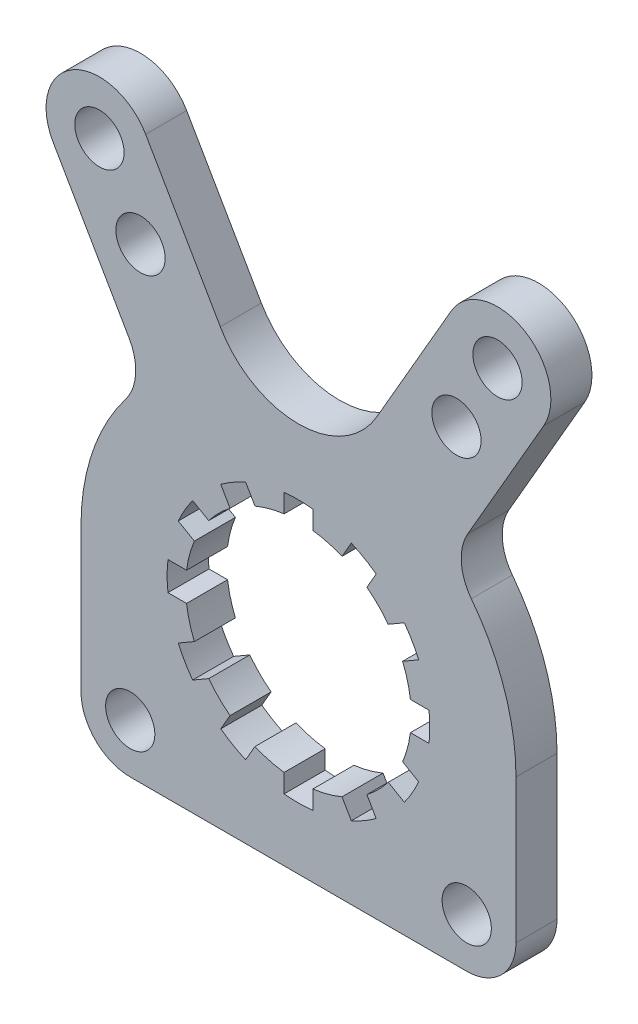
SolidWorks part; units mm, degrees
ref_plane "Alzado" through (0, 0, 0) normal (0, 0, 1) x (1, 0, 0)
ref_plane "Planta" through (0, 0, 0) normal (0, 1, 0) x (1, 0, 0)
ref_plane "Vista lateral" through (0, 0, 0) normal (1, 0, 0) x (0, 0, -1)
sketch "Croquis1" plane through (0, 0, 0) normal (0, 0, 1) x (1, 0, 0)
  line L0 (-59.7583, 77.5045) -> (-41.2583, 45.4615)
  line L5 (0, -79.3293) -> (0, 79.3293) construction
  line L7 (-99.8254, 0) -> (99.8254, 0) construction
  line L8 (-53, 0) -> (-53, -35)
  line L9 (-41, -47) -> (41, -47)
  line L11 (-48.5, 84.0045) -> (0, 0) construction
  line L12 (-37.2417, 90.5045) -> (-19.0526, 59)
  line L13 (37.2417, 90.5045) -> (19.0526, 59)
  line L14 (53, 0) -> (53, -35)
  line L15 (59.7583, 77.5045) -> (41.2583, 45.4615)
  arc A0 (-53, -35) -> (-41, -47) centre (-41, -35) ccw
  circle A8 centre (0, 0) radius 41 construction
  arc A10 (-37.2417, 90.5045) -> (-59.7583, 77.5045) centre (-48.5, 84.0045) ccw
  arc A11 (-41.2583, 45.4615) -> (-42.1151, 32.1763) centre (-51.6506, 39.4615) cw
  arc A12 (-42.1151, 32.1763) -> (-53, 0) centre (0, 0) ccw
  arc A13 (42.1151, 32.1763) -> (53, 0) centre (0, 0) cw
  arc A14 (41.2583, 45.4615) -> (42.1151, 32.1763) centre (51.6506, 39.4615) ccw
  arc A15 (37.2417, 90.5045) -> (59.7583, 77.5045) centre (48.5, 84.0045) cw
  arc A16 (53, -35) -> (41, -47) centre (41, -35) cw
  arc A17 (-19.0526, 59) -> (19.0526, 59) centre (0, 70) ccw
  circle A18 centre (0, 0) radius 53 construction
  point P2 (-38.5, 66.684)
  point P3 (-26.5, 45.8993)
  point P14 (0, -47)
  point P17 (0, 0)
  point P18 (-20.5, 35.507)
  point P22 (0, 0)
  point P35 (20.5, 35.507)
  point P36 (26.5, 45.8993)
  point P37 (38.5, 66.684)
  point P38 (0, 0)
  dimension "D1" = 24
  dimension "D2" = 24
  dimension "D4" = 82
  dimension "D5" = 13
  dimension "D7" = 82
  dimension "D8" = 12
  dimension "D3" = 20
  dimension "D11" = 22
  dimension "D6" = 30
  dimension "D9" = 35
extrude "Saliente-Extruir1" add sketch "Croquis1" along normal blind 10
sketch "Croquis2" plane through (0, 0, 10) normal (0, 0, 1) x (1, 0, 0)
  line L0 (-3.5, 31.808) -> (-3.5, 27.2764)
  line L1 (3.5, 31.808) -> (3.5, 27.2764)
  line L2 (-3.5, 29.5422) -> (3.5, 29.5422) construction
  line L3 (18.9351, 25.7966) -> (16.6693, 21.872)
  line L4 (12.8729, 29.2966) -> (10.6071, 25.372)
  line L5 (29.2966, 12.8729) -> (25.372, 10.6071)
  line L6 (25.7966, 18.9351) -> (21.872, 16.6693)
  line L7 (-53, 0) -> (-53, -35)
  line L8 (-41, -47) -> (41, -47)
  line L9 (53, -35) -> (53, 0)
  line L10 (41.2583, 45.4615) -> (59.7583, 77.5045)
  line L11 (37.2417, 90.5045) -> (19.0526, 59)
  line L12 (-19.0526, 59) -> (-37.2417, 90.5045)
  line L13 (-59.7583, 77.5045) -> (-41.2583, 45.4615)
  line L14 (-53, 0) -> (-53, -35)
  line L15 (-41, -47) -> (41, -47)
  line L16 (53, -35) -> (53, 0)
  line L17 (41.2583, 45.4615) -> (59.7583, 77.5045)
  line L18 (37.2417, 90.5045) -> (19.0526, 59)
  line L19 (-19.0526, 59) -> (-37.2417, 90.5045)
  line L20 (-59.7583, 77.5045) -> (-41.2583, 45.4615)
  line L21 (31.808, -3.5) -> (27.2764, -3.5)
  line L22 (31.808, 3.5) -> (27.2764, 3.5)
  line L23 (25.7966, -18.9351) -> (21.872, -16.6693)
  line L24 (29.2966, -12.8729) -> (25.372, -10.6071)
  line L25 (12.8729, -29.2966) -> (10.6071, -25.372)
  line L26 (18.9351, -25.7966) -> (16.6693, -21.872)
  line L27 (-3.5, -31.808) -> (-3.5, -27.2764)
  line L28 (3.5, -31.808) -> (3.5, -27.2764)
  line L29 (-18.9351, -25.7966) -> (-16.6693, -21.872)
  line L30 (-12.8729, -29.2966) -> (-10.6071, -25.372)
  line L31 (-29.2966, -12.8729) -> (-25.372, -10.6071)
  line L32 (-25.7966, -18.9351) -> (-21.872, -16.6693)
  line L33 (-31.808, 3.5) -> (-27.2764, 3.5)
  line L34 (-31.808, -3.5) -> (-27.2764, -3.5)
  line L35 (-25.7966, 18.9351) -> (-21.872, 16.6693)
  line L36 (-29.2966, 12.8729) -> (-25.372, 10.6071)
  line L37 (-12.8729, 29.2966) -> (-10.6071, 25.372)
  line L38 (-18.9351, 25.7966) -> (-16.6693, 21.872)
  line L39 (-48.5, 84.0045) -> (0, 0) construction
  line L40 (0, 0) -> (48.5, 84.0045) construction
  arc A0 (3.5, 31.808) -> (-3.5, 31.808) centre (0, 0) ccw
  arc A1 (-3.5, 27.2764) -> (-10.6071, 25.372) centre (0, 0) ccw
  arc A2 (18.9351, 25.7966) -> (12.8729, 29.2966) centre (0, 0) ccw
  arc A3 (29.2966, 12.8729) -> (25.7966, 18.9351) centre (0, 0) ccw
  arc A4 (31.808, -3.5) -> (31.808, 3.5) centre (0, 0) ccw
  arc A5 (25.7966, -18.9351) -> (29.2966, -12.8729) centre (0, 0) ccw
  arc A6 (12.8729, -29.2966) -> (18.9351, -25.7966) centre (0, 0) ccw
  arc A7 (-3.5, -31.808) -> (3.5, -31.808) centre (0, 0) ccw
  arc A8 (-18.9351, -25.7966) -> (-12.8729, -29.2966) centre (0, 0) ccw
  arc A9 (-42.1151, 32.1763) -> (-41.2583, 45.4615) centre (-51.6506, 39.4615) ccw
  arc A10 (-42.1151, 32.1763) -> (-53, 0) centre (0, 0) ccw
  arc A11 (-53, -35) -> (-41, -47) centre (-41, -35) ccw
  arc A12 (41, -47) -> (53, -35) centre (41, -35) ccw
  arc A13 (53, 0) -> (42.1151, 32.1763) centre (0, 0) ccw
  arc A14 (41.2583, 45.4615) -> (42.1151, 32.1763) centre (51.6506, 39.4615) ccw
  arc A15 (59.7583, 77.5045) -> (37.2417, 90.5045) centre (48.5, 84.0045) ccw
  arc A16 (-19.0526, 59) -> (19.0526, 59) centre (0, 70) ccw
  arc A17 (-37.2417, 90.5045) -> (-59.7583, 77.5045) centre (-48.5, 84.0045) ccw
  arc A18 (-42.1151, 32.1763) -> (-41.2583, 45.4615) centre (-51.6506, 39.4615) ccw
  arc A19 (-42.1151, 32.1763) -> (-53, 0) centre (0, 0) ccw
  arc A20 (-53, -35) -> (-41, -47) centre (-41, -35) ccw
  arc A21 (41, -47) -> (53, -35) centre (41, -35) ccw
  arc A22 (53, 0) -> (42.1151, 32.1763) centre (0, 0) ccw
  arc A23 (41.2583, 45.4615) -> (42.1151, 32.1763) centre (51.6506, 39.4615) ccw
  arc A24 (59.7583, 77.5045) -> (37.2417, 90.5045) centre (48.5, 84.0045) ccw
  arc A25 (-19.0526, 59) -> (19.0526, 59) centre (0, 70) ccw
  arc A26 (-37.2417, 90.5045) -> (-59.7583, 77.5045) centre (-48.5, 84.0045) ccw
  arc A27 (-29.2966, -12.8729) -> (-25.7966, -18.9351) centre (0, 0) ccw
  arc A28 (-31.808, 3.5) -> (-31.808, -3.5) centre (0, 0) ccw
  arc A29 (-25.7966, 18.9351) -> (-29.2966, 12.8729) centre (0, 0) ccw
  arc A30 (-12.8729, 29.2966) -> (-18.9351, 25.7966) centre (0, 0) ccw
  arc A31 (10.6071, 25.372) -> (3.5, 27.2764) centre (0, 0) ccw
  arc A32 (21.872, 16.6693) -> (16.6693, 21.872) centre (0, 0) ccw
  arc A33 (27.2764, 3.5) -> (25.372, 10.6071) centre (0, 0) ccw
  arc A34 (25.372, -10.6071) -> (27.2764, -3.5) centre (0, 0) ccw
  arc A35 (16.6693, -21.872) -> (21.872, -16.6693) centre (0, 0) ccw
  arc A36 (3.5, -27.2764) -> (10.6071, -25.372) centre (0, 0) ccw
  arc A37 (-10.6071, -25.372) -> (-3.5, -27.2764) centre (0, 0) ccw
  arc A38 (-21.872, -16.6693) -> (-16.6693, -21.872) centre (0, 0) ccw
  arc A39 (-25.372, 10.6071) -> (-27.2764, 3.5) centre (0, 0) ccw
  arc A40 (-16.6693, 21.872) -> (-21.872, 16.6693) centre (0, 0) ccw
  circle A41 centre (-41, -35) radius 6
  circle A42 centre (41, -35) radius 6
  circle A43 centre (-48.5, 84.0045) radius 6
  circle A44 centre (48.5, 84.0045) radius 6
  circle A45 centre (-38.5, 66.684) radius 6
  circle A46 centre (38.5, 66.684) radius 6
  arc A47 (-27.2764, -3.5) -> (-25.372, -10.6071) centre (0, 0) ccw
  point P18 (0, 29.5422)
  point P79 (0, 0)
  dimension "D2" = 64
  dimension "D3" = 55
  dimension "D6" = 12
  dimension "D4" = 7
  dimension "D7" = 20
  dimension "D8" = 20
  dimension "D1" = 0
  dimension "D5" = 12
extrude "Cortar-Extruir3" cut sketch "Croquis2" against normal through all contours L36 A39 L33 A28 L34 A47 L31 A27 L32 A38 L29 A8 L30 A37 L27 A7 L28 A36 L25 A6 L26 A35 L23 A5 L24 A34 L21 A4 L22 A33 L5 A3 L6 A32 L3 A2 L4 A31 L1 A0 L0 A1 L37 A30 L38 A40 L35 A29 | A46 | A44 | A43 | A45 | A41 | A42
